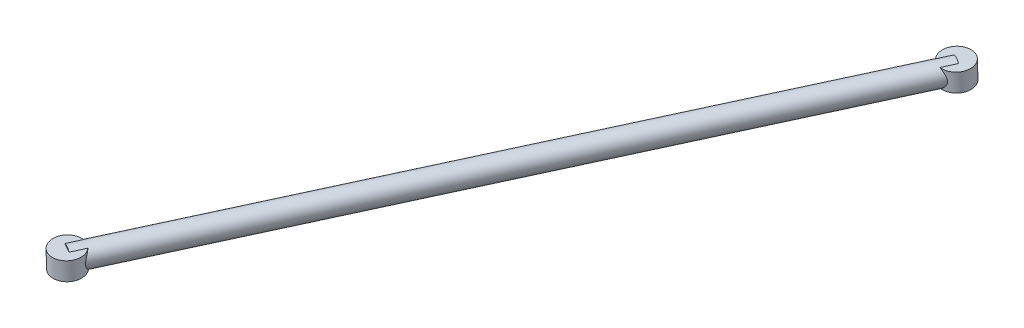
SolidWorks part; units mm, degrees
ref_plane "Plano frontal" through (0, 0, 0) normal (0, 0, 1) x (1, 0, 0)
ref_plane "Plano superior" through (0, 0, 0) normal (0, 1, 0) x (1, 0, 0)
ref_plane "Plano direito" through (0, 0, 0) normal (1, 0, 0) x (0, 0, -1)
sketch3d "SUSP_FL_pushrod_eixo"
  line L0 (-535.6, -114.51, -83.23) -> (-308.5607, -96.2566, -516.2583)
sweep "SUSP_FL_pushrod" add path "SUSP_FL_pushrod_eixo" circular profile diameter 16 parameters "D3"=16
sketch3d "SUSP_FL_pushrod_rod_end_mount_eixo"
  line L0 (-535.7358, -121.4991, -83.5961) -> (-535.4642, -107.5209, -82.8639)
sweep "SUSP_FL_pushrod_rod_end_mount" add path "SUSP_FL_pushrod_rod_end_mount_eixo" circular profile diameter 22 parameters "D3"=22
sketch3d "SUSP_FL_pushrod_rod_end_rocker_eixo"
  line L0 (-308.6965, -103.2457, -516.6244) -> (-308.4249, -89.2675, -515.8922)
sweep "SUSP_FL_pushrod_rod_end_rocker" add path "SUSP_FL_pushrod_rod_end_rocker_eixo" circular profile diameter 22 parameters "D3"=22
sketch3d "REF_SKETCH"
  line L0 (-539.6, -116.91, -85.03) -> (-531.6, -112.11, -81.43)
  line L1 (-533.2, -117.51, -86.43) -> (-538, -111.51, -80.03)
  line L2 (-312.5607, -98.6566, -518.0583) -> (-304.5607, -93.8566, -514.4583)
  line L3 (-306.1607, -99.2566, -519.4583) -> (-310.9607, -93.2566, -513.0583)
ref_point "P_MOUNT"
ref_point "P_ROCKER"
